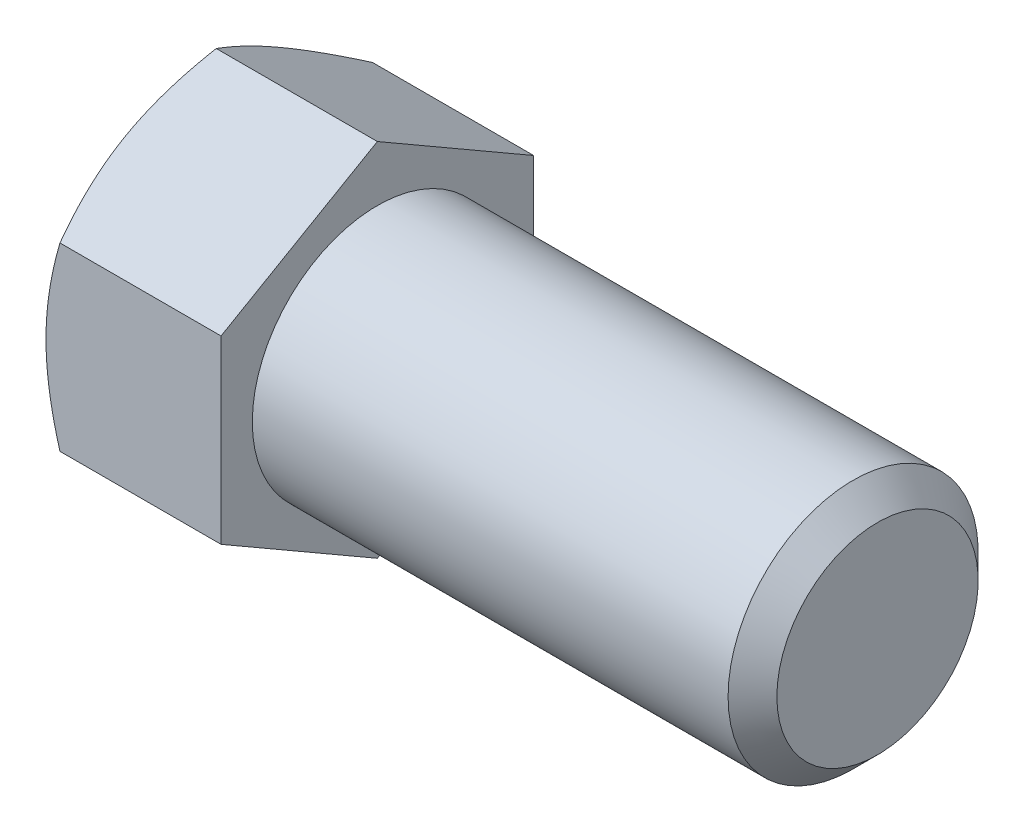
SolidWorks part; units mm, degrees
extrude "BaseHead" add sketch "Sketch1" along normal blind 2.8
sketch "Sketch1" plane through (0, 0, 0) normal (1, 0, 0) x (0, 0, -1)
  line L0 (2.5, 1.4434) -> (2.5, -1.4434)
  line L1 (-2.5, 1.4434) -> (-2.5, -1.4434)
  line L2 (2.5, -1.4434) -> (0, -2.8868)
  line L3 (0, -2.8868) -> (-2.5, -1.4434)
  line L4 (2.5, 1.4434) -> (0, 2.8868)
  line L5 (0, 2.8868) -> (-2.5, 1.4434)
  dimension "Width_flats" = 5
  dimension "D2" = 120
  dimension "D3" = 2.5
  dimension "D4" = 2.5
  dimension "D5" = 2.5
ref_plane "Plane1" through (0, 0, 0) normal (0, 0, 1) x (1, 0, 0)
ref_plane "Plane2" through (0, 0, 0) normal (0, 1, 0) x (1, 0, 0)
ref_plane "Plane3" through (0, 0, 0) normal (1, 0, 0) x (0, 0, -1)
sketch "BodySke" plane through (0, 0, 0) normal (0, 0, 1) x (1, 0, 0)
  line L1 (0, 0) -> (10.8, 0)
  line L2 (0, 0) -> (0, 2)
  line L4 (10.8, 0) -> (10.8, 1.61)
  line L5 (2.8, 2.8868) -> (2.8, 1.4434) construction
  line L6 (10.8, 1.61) -> (10.41, 2)
  line L7 (0, 0) -> (110.49, 0) construction
  line L8 (10.8, -1.61) -> (10.41, -2) construction
  line L9 (0, 1.4434) -> (0, -1.4434) construction
  line L10 (3.5, 15.24) -> (3.5, -1.27) construction
  line L11 (-3.2, 15.24) -> (-3.2, -1.27) construction
  line L12 (2.8, 1.4434) -> (2.8, -1.4434) construction
  line L15 (0, 2) -> (10.41, 2)
  dimension "Body_ch_ang" = 45
  dimension "Minor_dia" = 3.22
  dimension "Diameter" = 4
revolve "BaseBody" add sketch "BodySke" angle 360 about L7
cosmetic thread "ThreadCosmetic" parameters "Thread_length"=7.3, "Thread_minor"=3.22
fillet "HeadFillet" [suppressed] radius 0.2
sketch "Sketch3" plane through (0, 0, 0) normal (0, 0, 1) x (1, 0, 0)
  line L0 (0, 2.5) -> (3.11, 7.8868)
  line L1 (0, 2.8868) -> (0, 1.4434) construction
  line L2 (3.11, 7.8868) -> (3.11, 12.8868)
  line L3 (3.11, 12.8868) -> (-10, 12.8868)
  line L4 (-10, 12.8868) -> (-10, 2.5)
  line L5 (-10, 2.5) -> (0, 2.5)
  line L6 (0, 0) -> (99.06, 0) construction
  line L7 (2.8, 2.8868) -> (0, 2.8868) construction
  dimension "D1" = 2.5
  dimension "D2" = 5
  dimension "D3" = 10
  dimension "D4" = 5
  dimension "Head_ch_ang" = 30
revolve "HeadChamfer" cut sketch "Sketch3" angle 360 about L6
sketch "ThdSchSke" plane through (0, 0, 0) normal (0, 0, 1) x (1, 0, 0)
  line L0 (3.5, -1.61) -> (3.2269, -2)
  line L1 (3.5, -1.61) -> (3.7731, -2)
  line L2 (3.7731, -2) -> (3.7731, -2.5)
  line L3 (-3.175, 0) -> (5.1513, 0) construction
  line L5 (3.7731, -2.5) -> (3.2269, -2.5)
  line L6 (3.2269, -2.5) -> (3.2269, -2)
  dimension "Thread_minor" = 3.22
  dimension "Diameter" = 4
  dimension "Start" = 3.5
revolve "ThreadSchematic" [suppressed] cut sketch "ThdSchSke" angle 360 about L3
pattern_linear "ThdSchPat" [suppressed]
equation "\"D3@Sketch1\" = \"Width_flats@Sketch1\" / 2"
equation "\"D4@Sketch1\" = \"D3@Sketch1\""
equation "\"D5@Sketch1\" = \"D4@Sketch1\""
equation "\"Thread_minor@ThreadCosmetic\" = \"Minor_dia@BodySke\""
equation "\"D1@Sketch3\" = \"Width_flats@Sketch1\" / 2"
equation "\"Thread_length@ThreadCosmetic\" = ((sgn( (\"Length@BodySke\" - \"Advance@BodySke\" ) - \"Thread_nom@BodySke\" )-1)*( (\"Length@BodySke\" - \"Advance@BodySke\" ) - \"Thread_nom@BodySke\" ))/-2+ \"Thread_nom@BodySke\""
equation "\"Thread_minor@ThdSchSke\" = \"Minor_dia@BodySke\""
equation "\"Diameter@ThdSchSke\" = \"Diameter@BodySke\""
equation "\"Overcut@ThdSchSke\" = \"Diameter@BodySke\" * 1.25"
equation "\"Start@ThdSchSke\" = \"Head_ht@BaseHead\" + \"Length@BodySke\" - \"Thread_length@ThreadCosmetic\"  '---Non-countersunk---"
equation "\"Num_threads@ThdSchPat\" = int( \"Thread_length@ThreadCosmetic\" / \"Advance@BodySke\" + 0.999 )  + 1"
equation "\"Advance@ThdSchPat\" = \"Thread_length@ThreadCosmetic\" /  (\"Num_threads@ThdSchPat\" - 1) 'relax it"
equation "\"Num_threads@ThdSchPat\" = \"Num_threads@ThdSchPat\" - sgn( \"Num_threads@ThdSchPat\" - 1) '---chamfered tips only---"
